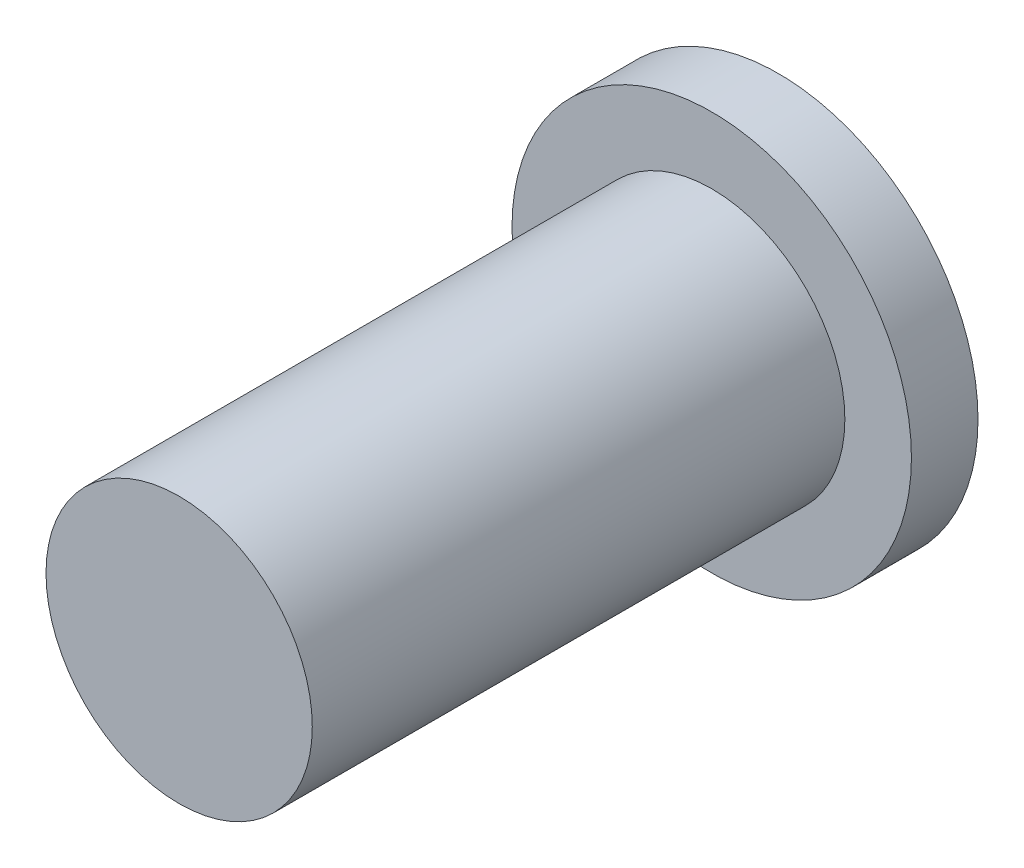
SolidWorks part; units mm, degrees
material "Acrylic (Medium-high impact)"
ref_plane "Front Plane" through (0, 0, 0) normal (0, 0, 1) x (1, 0, 0)
ref_plane "Top Plane" through (0, 0, 0) normal (0, 1, 0) x (1, 0, 0)
ref_plane "Right Plane" through (0, 0, 0) normal (1, 0, 0) x (0, 0, -1)
sketch "Sketch1" plane through (0, 0, 0) normal (0, 0, 1) x (1, 0, 0)
  circle A0 centre (0, 0) radius 3.81
  dimension "D1" = 7.62
extrude "Boss-Extrude1" add sketch "Sketch1" along normal blind 1.27
sketch "Sketch2" plane through (0, 0, 1.27) normal (0, 0, 1) x (1, 0, 0)
  circle A0 centre (0, 0) radius 2.54
  dimension "D1" = 5.08
extrude "Boss-Extrude2" add sketch "Sketch2" along normal blind 10.16
